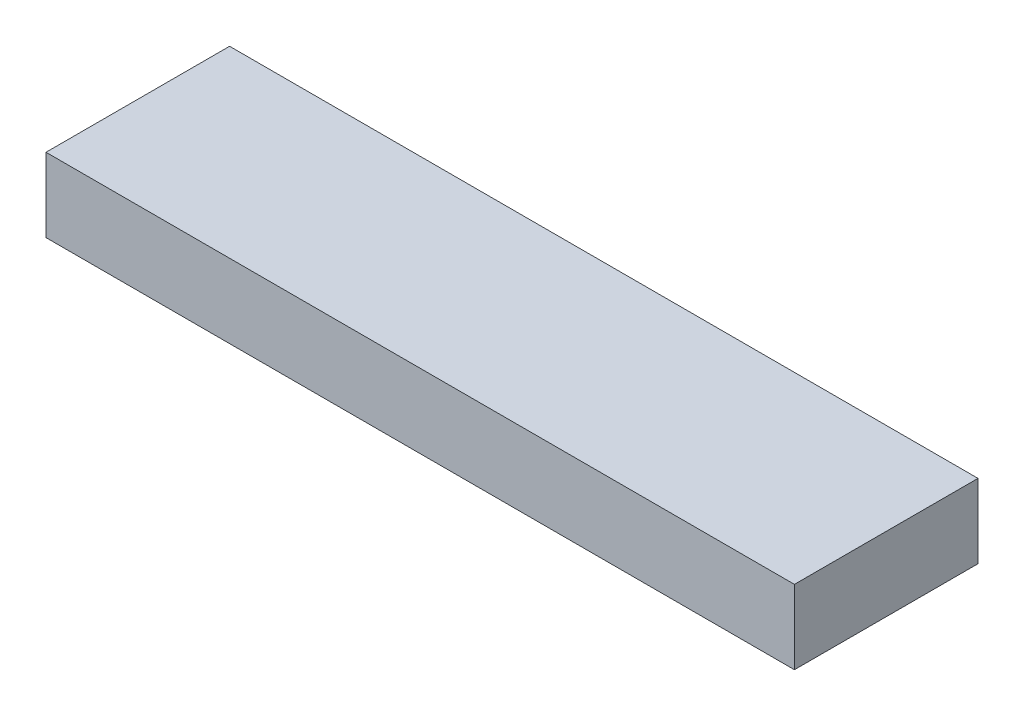
SolidWorks part; units mm, degrees
ref_plane "Front Plane" through (0, 0, 0) normal (0, 0, 1) x (1, 0, 0)
ref_plane "Top Plane" through (0, 0, 0) normal (0, 1, 0) x (1, 0, 0)
ref_plane "Right Plane" through (0, 0, 0) normal (1, 0, 0) x (0, 0, -1)
sketch "Sketch1" plane through (0, 0, 0) normal (0, 1, 0) x (1, 0, 0)
  line L1 (-15.94, 3.91) -> (15.94, 3.91)
  line L2 (-15.94, 3.91) -> (-15.94, -3.91)
  line L3 (-15.94, -3.91) -> (15.94, -3.91)
  line L4 (15.94, 3.91) -> (15.94, -3.91)
  line L5 (-15.94, 3.91) -> (15.94, -3.91) construction
  line L6 (-15.94, -3.91) -> (15.94, 3.91) construction
  point P0 (0, 0)
  dimension "D1" = 31.88
  dimension "D2" = 7.82
extrude "Boss-Extrude1" add sketch "Sketch1" against normal blind 3.15
shell "Shell1" thickness 1.6
sketch "Sketch2" plane through (0, -1.6, 0) normal (0, -1, 0) x (1, 0, 0)
  line L1 (-15.94, -3.91) -> (-15.94, 3.91) construction
  line L2 (15.94, -3.91) -> (-15.94, -3.91) construction
  circle A0 centre (-7.97, 0) radius 1.475
  circle A1 centre (-7.97, 0) radius 0.7
  circle A2 centre (0, 0) radius 0.7
  circle A3 centre (0, 0) radius 1.475
  circle A4 centre (7.97, 0) radius 0.7
  circle A5 centre (7.97, 0) radius 1.475
  dimension "D3" = 3.91
  dimension "D4" = 2.95
  dimension "D5" = 1.4
  dimension "D6" = 7.97
  dimension "D1" = 7.97
  dimension "D2" = 3
extrude "Boss-Extrude2" add sketch "Sketch2" along normal offset from surface (1.35 mm away) 0.2 up to face at (0, -3.15, 0)
